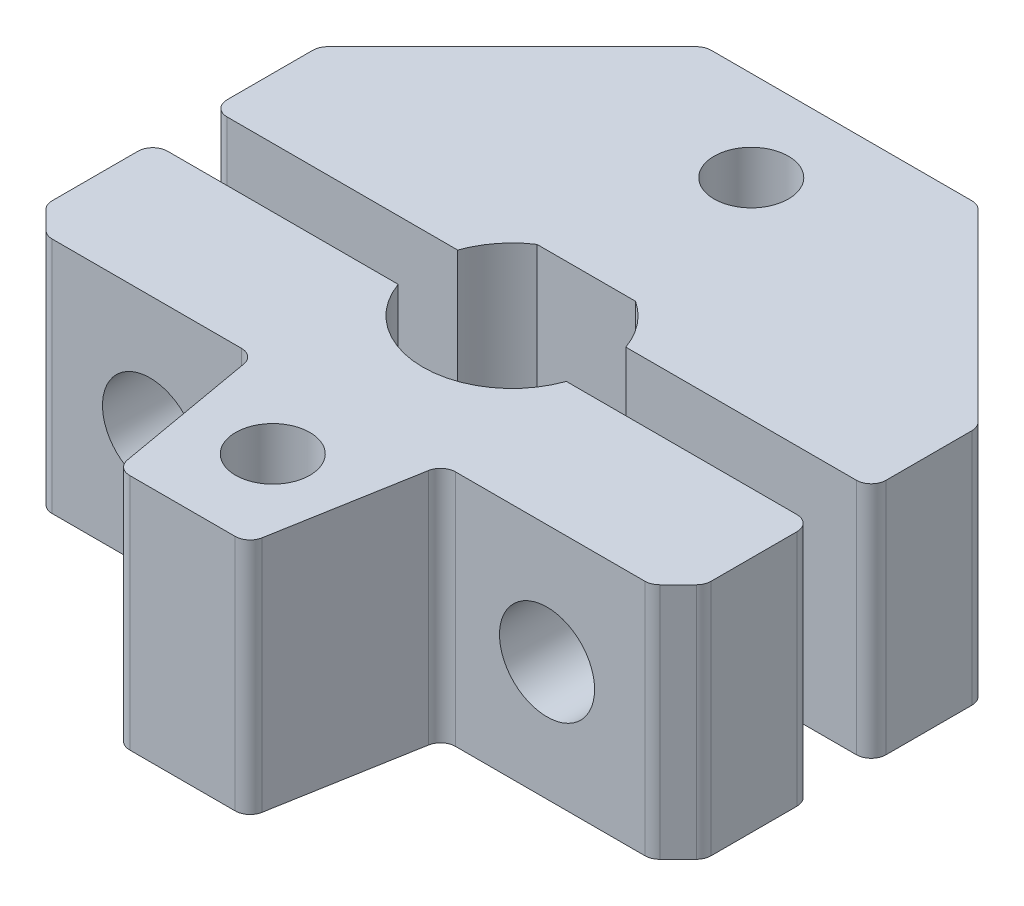
SolidWorks part; units mm, degrees
ref_plane "前视基准面" through (0, 0, 0) normal (0, 0, 1) x (1, 0, 0)
ref_plane "上视基准面" through (0, 0, 0) normal (0, 1, 0) x (1, 0, 0)
ref_plane "右视基准面" through (0, 0, 0) normal (1, 0, 0) x (0, 0, -1)
other "Configuration Table"
sketch "草图1" plane through (0, 0, 0) normal (0, 1, 0) x (1, 0, 0)
  line L0 (4.5922, 11.0866) -> (-4.5922, 11.0866)
  line L1 (2.8284, 1) -> (11.0866, 1)
  line L2 (-4.5922, 11.0866) -> (-11.0866, 4.5922)
  line L3 (-11.0866, 4.5922) -> (-11.0866, -4.5922)
  line L4 (-11.0866, -4.5922) -> (-4.5922, -11.0866)
  line L5 (-4.5922, -11.0866) -> (4.5922, -11.0866)
  line L6 (4.5922, -11.0866) -> (11.0866, -4.5922)
  line L7 (11.0866, -4.5922) -> (11.0866, 4.5922)
  line L8 (11.0866, 4.5922) -> (4.5922, 11.0866)
  line L9 (1.6583, 2.5) -> (-1.6583, 2.5)
  line L10 (2.8284, -1) -> (11.0866, -1)
  line L11 (-11.0866, 1) -> (-2.8284, 1)
  line L12 (-11.0866, -1) -> (-2.8284, -1)
  line L13 (-10.1788, -5.5) -> (-3.1788, -5.5)
  line L15 (0, 0) -> (-11.0866, 0) construction
  line L16 (-3.1788, -5.5) -> (-2.1937, -11.0866)
  line L17 (0, 0) -> (0, -11.0866) construction
  line L18 (3.1788, -5.5) -> (2.1937, -11.0866)
  line L19 (10.1788, -5.5) -> (3.1788, -5.5)
  circle A0 centre (0, 0) radius 12 construction
  arc A1 (2.8284, 1) -> (1.6583, 2.5) centre (0, 0) ccw
  circle A3 centre (0, -8.05) radius 1
  circle A4 centre (0, 0) radius 8.05 construction
  circle A5 centre (0, 8.05) radius 1
  arc A6 (-2.8284, -1) -> (2.8284, -1) centre (0, 0) ccw
  arc A7 (-1.6583, 2.5) -> (-2.8284, 1) centre (0, 0) ccw
  dimension "D1" = 6
  dimension "D4" = 24
  dimension "D5" = 2
  dimension "D2" = 16.1
  dimension "D3" = 2.5
  dimension "D6" = 2
  dimension "D7" = 7
  dimension "D8" = 4.5
  dimension "D10" = 100
extrude "凸台-拉伸1" add sketch "草图1" along normal blind 8 contours A7 L9 A1 L1 L7 L8 L0 L2 L3 L11 A5 | A6 L12 L3 L4 L13 L16 L5 L18 L19 L6 L7 L10 A3
sketch "草图3" plane through (0, 0, 5.5) normal (0, 0, 1) x (1, 0, 0)
  line L0 (0, 4) -> (-11.0866, 4) construction
  line L1 (0, 4) -> (0, 0) construction
  line L2 (-2.1937, 0) -> (2.1937, 0) construction
  line L3 (-11.0866, 8) -> (-11.0866, 0) construction
  line L4 (-6.6788, 4) -> (-6.6788, 8) construction
  line L5 (-10.1788, 8) -> (-3.1788, 8) construction
  circle A0 centre (-6.6788, 4) radius 1
  circle A1 centre (6.6788, 4) radius 1
  point P8 (-6.5, 4)
  point P12 (-6.6788, 5.1444)
  dimension "D1" = 2
extrude "切除-拉伸1" cut sketch "草图3" against normal through all
sketch "草图4" plane through (0, 0, 5.5) normal (0, 0, 1) x (1, 0, 0)
  circle A0 centre (-6.6788, 4) radius 1.6
  circle A1 centre (6.6788, 4) radius 1.6
  dimension "D1" = 3.2
extrude "切除-拉伸2" cut sketch "草图4" against normal up to surface (4.5 mm away) up to face at (5.6788, 4, 1)
fillet "圆角1" radius 0.5 6 edges at (11.0866, 4, -1) (11.0866, 4, -4.5922) (4.5922, 4, -11.0866) (-4.5922, 4, -11.0866) (-11.0866, 4, -4.5922) (-11.0866, 4, -1)
fillet "圆角2" radius 0.5 10 edges at (-11.0866, 4, 1) (-11.0866, 4, 4.5922) (-10.1788, 4, 5.5) (-3.1788, 4, 5.5) (-2.1937, 4, 11.0866) (2.1937, 4, 11.0866) (3.1788, 4, 5.5) (10.1788, 4, 5.5) (11.0866, 4, 4.5922) (11.0866, 4, 1)
hole_wizard "M3 螺纹孔6" positions "草图9" profile "草图10" tap size "M3" standard "GB" end condition through all
sketch "草图9" plane through (0, 8, 0) normal (0, 1, 0) x (1, 0, 0)
  point P0 (0, 8.05)
  point P3 (0, -8.05)
sketch "草图10" plane through (0, 8, -8.05) normal (1, 0, 0) x (0, 0, 1)
  line L0 (0, 0) -> (0, 8)
  line L1 (0, 8) -> (1.25, 8)
  line L2 (1.25, 8) -> (1.25, 0)
  line L5 (1.25, 0) -> (0, 0)
  line L11 (0, -6.35) -> (0, 107.95) construction
  dimension "通孔螺纹孔钻头直径" = 2.5
  dimension "通孔螺纹孔钻头深度" = 8
cosmetic thread "孔螺纹线5" parameters "D2"=3
cosmetic thread "孔螺纹线6" parameters "D2"=3
hole_wizard "M3 螺纹孔7" positions "草图11" profile "草图12" tap size "M3" standard "GB" end condition through all
sketch "草图11" plane through (0, 0, -1) normal (0, 0, 1) x (1, 0, 0)
  point P0 (6.6788, 4)
  point P3 (-6.6788, 4)
sketch "草图12" plane through (6.6788, 4, -1) normal (1, 0, 0) x (0, -1, 0)
  line L0 (0, 0) -> (0, 10.0866)
  line L1 (0, 10.0866) -> (1.25, 10.0866)
  line L2 (1.25, 10.0866) -> (1.25, 0)
  line L5 (1.25, 0) -> (0, 0)
  line L11 (0, -6.35) -> (0, 31.9478) construction
  point P3 (0, 31.9478)
  dimension "通孔螺纹孔钻头直径" = 2.5
  dimension "通孔螺纹孔钻头深度" = 10.0866
cosmetic thread "孔螺纹线7" parameters "D2"=3
cosmetic thread "孔螺纹线8" parameters "D2"=3
